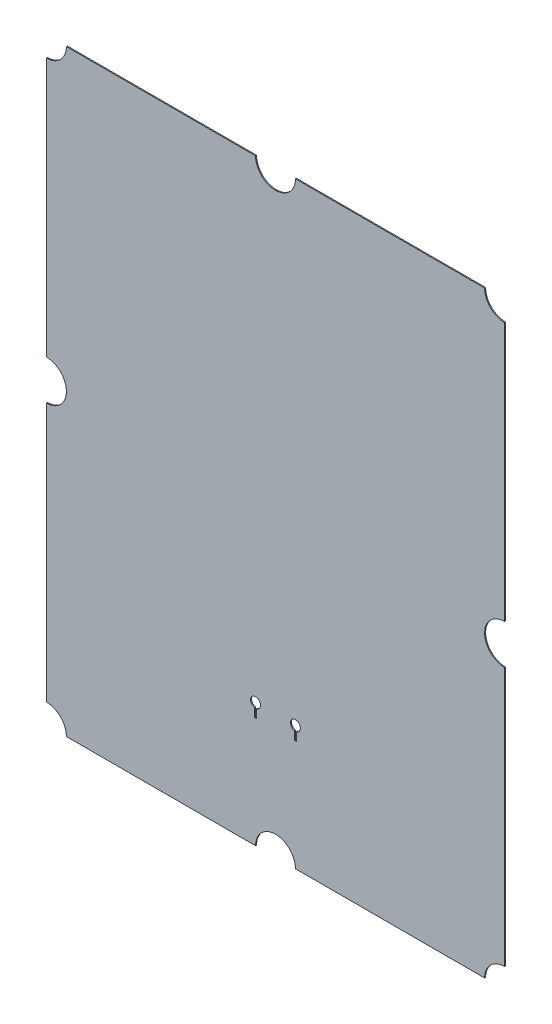
SolidWorks part; units mm, degrees
ref_plane "Front Plane" through (0, 0, 0) normal (0, 0, 1) x (1, 0, 0)
ref_plane "Top Plane" through (0, 0, 0) normal (0, 1, 0) x (1, 0, 0)
ref_plane "Right Plane" through (0, 0, 0) normal (1, 0, 0) x (0, 0, -1)
ref_plane "Plane1" through (0, 0, 0) normal (0, 0, -1) x (-1, 0, 0)
sketch "Sketch1" plane through (0, 0, 0) normal (0, 0, -1) x (-1, 0, 0)
  line L0 (105, 150) -> (10, 150)
  line L1 (-10, 150) -> (-105, 150)
  line L2 (-115, 140) -> (-115, 10)
  line L3 (-115, -10) -> (-115, -140)
  line L4 (-105, -150) -> (-10, -150)
  line L5 (10, -150) -> (105, -150)
  line L6 (115, -140) -> (115, -10)
  line L7 (115, 10) -> (115, 140)
  line L8 (9.5, -94.4484) -> (9.5, -90.1418)
  line L9 (10.5, -90.1418) -> (10.5, -94.4484)
  line L10 (10.5, -94.4484) -> (9.5, -94.4484)
  line L11 (-10.5, -94.4484) -> (-10.5, -90.1418)
  line L12 (-9.5, -90.1418) -> (-9.5, -94.4484)
  line L13 (-9.5, -94.4484) -> (-10.5, -94.4484)
  arc A0 (10, 150) -> (-10, 150) centre (0, 150) cw
  arc A1 (-105, 150) -> (-115, 140) centre (-115, 150) cw
  arc A2 (-115, 10) -> (-115, -10) centre (-115, 0) cw
  arc A3 (-115, -140) -> (-105, -150) centre (-115, -150) cw
  arc A4 (-10, -150) -> (10, -150) centre (0, -150) cw
  arc A5 (105, -150) -> (115, -140) centre (115, -150) cw
  arc A6 (115, -10) -> (115, 10) centre (115, 0) cw
  arc A7 (115, 140) -> (105, 150) centre (115, 150) cw
  arc A8 (9.5, -90.1418) -> (10.5, -90.1418) centre (10, -87.6923) cw
  arc A9 (-10.5, -90.1418) -> (-9.5, -90.1418) centre (-10, -87.6923) cw
extrude "Boss-Extrude1" add sketch "Sketch1" against normal blind 0.5
ref_plane "Plane2" through (0, 0, 0) normal (1, 0, 0) x (0, 0, -1)
ref_plane "Plane3" through (0, 0, 0) normal (0, 1, 0) x (1, 0, 0)
